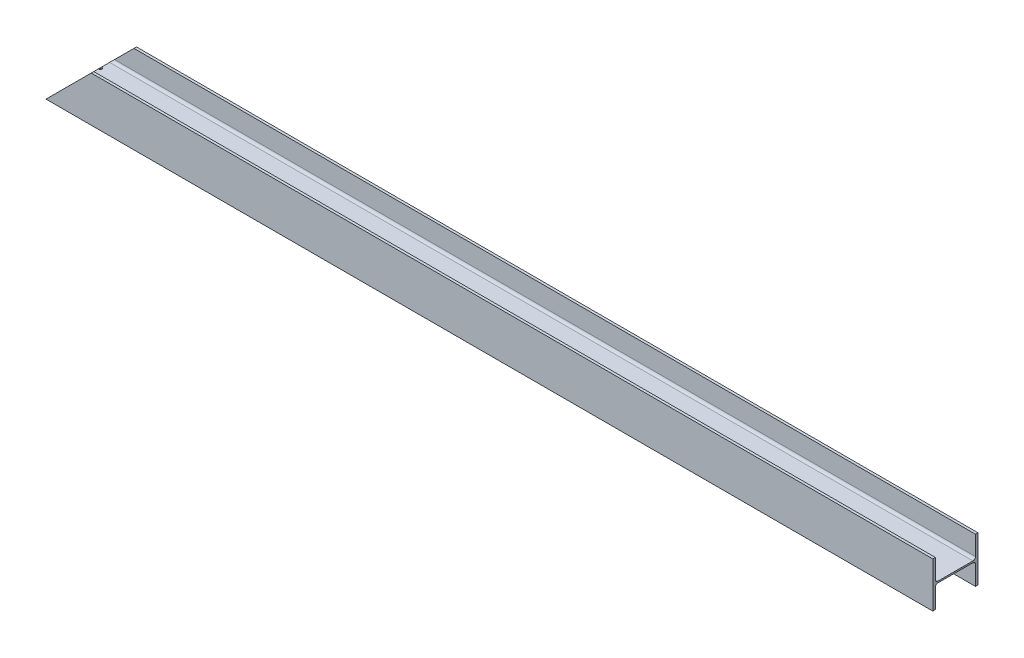
SolidWorks part; units mm, degrees
material "AISI 304 [Custom]"
ref_plane "Front" through (0, 0, 0) normal (0, 0, 1) x (1, 0, 0)
ref_plane "Top" through (0, 0, 0) normal (0, 1, 0) x (1, 0, 0)
ref_plane "Right" through (0, 0, 0) normal (1, 0, 0) x (0, 0, -1)
sketch3d "3DSketch1"
  line L0 (0, 0, 0) -> (-5000, 0, 0) construction
  line L1 (0, 0, 0) -> (-5000, 0, 0)
other "Universal Column_ics 250UC72.9(1)"
ref_plane "Plane1" through (0, 0, 0) normal (-1, 0, 0) x (0, 1, 0)
sketch "Sketch1" plane through (0, 0, 0) normal (-1, 0, 0) x (0, 1, 0)
  line L0 (0, -127) -> (0, 127) construction
  line L1 (-127, -127) -> (127, -127)
  line L2 (127, -127) -> (127, -112.8)
  line L3 (-127, -127) -> (-127, -112.8)
  line L4 (127, -112.8) -> (18.3, -112.8)
  line L5 (-127, -112.8) -> (-18.3, -112.8)
  line L6 (4.3, -98.8) -> (4.3, 98.8)
  line L7 (-4.3, -98.8) -> (-4.3, 98.8)
  line L8 (-127, 112.8) -> (-18.3, 112.8)
  line L9 (-4.3, 0) -> (4.3, 0) construction
  line L10 (127, 112.8) -> (18.3, 112.8)
  line L11 (-127, 127) -> (-127, 112.8)
  line L12 (127, 127) -> (127, 112.8)
  line L13 (-127, 127) -> (127, 127)
  line L14 (127, 112.8) -> (127, -112.8) construction
  line L15 (-127, 112.8) -> (-127, -112.8) construction
  arc A2 (18.3, -112.8) -> (4.3, -98.8) centre (18.3, -98.8) cw
  arc A3 (-18.3, -112.8) -> (-4.3, -98.8) centre (-18.3, -98.8) ccw
  arc A4 (-18.3, 112.8) -> (-4.3, 98.8) centre (-18.3, 98.8) cw
  arc A5 (18.3, 112.8) -> (4.3, 98.8) centre (18.3, 98.8) ccw
  point P6 (0, 0)
  point P9 (127, 0)
  point P10 (-127, 0)
  point P27 (0, 0)
  dimension "R1" = 14
  dimension "Width" = 254
  dimension "Web" = 8.6
  dimension "Height" = 254
  dimension "Flange" = 14.2
extrude "Cut-Extrude2" cut sketch "Sketch3" against normal blind 14.2
sketch "Sketch3" plane through (-4890.5, 0, -127) normal (0, 0, -1) x (0, -1, 0)
  circle A2 centre (48, -33.5) radius 9
  circle A4 centre (48, 14.5) radius 9
  circle A6 centre (-48, -33.5) radius 9
  circle A8 centre (-48, 14.5) radius 9
extrude "Cut-Extrude19" cut sketch "Sketch20" against normal mid plane 8.6
sketch "Sketch20" plane through (-4890.5, 0, 0) normal (0, 1, 0) x (0, 0, -1)
  circle A2 centre (45, -33.5) radius 9
  circle A4 centre (-45, -33.5) radius 9
  circle A6 centre (45, 14.5) radius 9
  circle A8 centre (-45, 14.5) radius 9
extrude "Cut-Extrude20" cut sketch "Sketch21" against normal blind 10
sketch "Sketch21" plane through (-5000, 0, 0) normal (-1, 0, 0) x (0, 1, 0)
  line L8 (127, 127) -> (-127, 127)
  line L9 (127, -127) -> (127, 127)
  line L10 (-127, -127) -> (127, -127)
  line L11 (-127, 127) -> (-127, -127)
extrude "Cut-Extrude21" cut sketch "Sketch22" along normal blind 10
sketch "Sketch22" plane through (0, 0, 0) normal (-1, 0, 0) x (0, 1, 0)
  line L8 (141, 141) -> (-141, 141)
  line L9 (141, -141) -> (141, 141)
  line L10 (-141, -141) -> (141, -141)
  line L11 (-141, 141) -> (-141, -141)
sketch "Sketch23" plane through (0, 0, 127) normal (0, 0, 1) x (1, 0, 0)
  line L0 (-4990, -127) -> (-4736, 127)
  line L1 (-4990, 127) -> (-10, 127) construction
  line L2 (-4736, 127) -> (-4990, 127)
  line L3 (-4990, 127) -> (-4990, -127)
  dimension "D1" = 135
extrude "Cut-Extrude22" cut sketch "Sketch23" against normal through all
